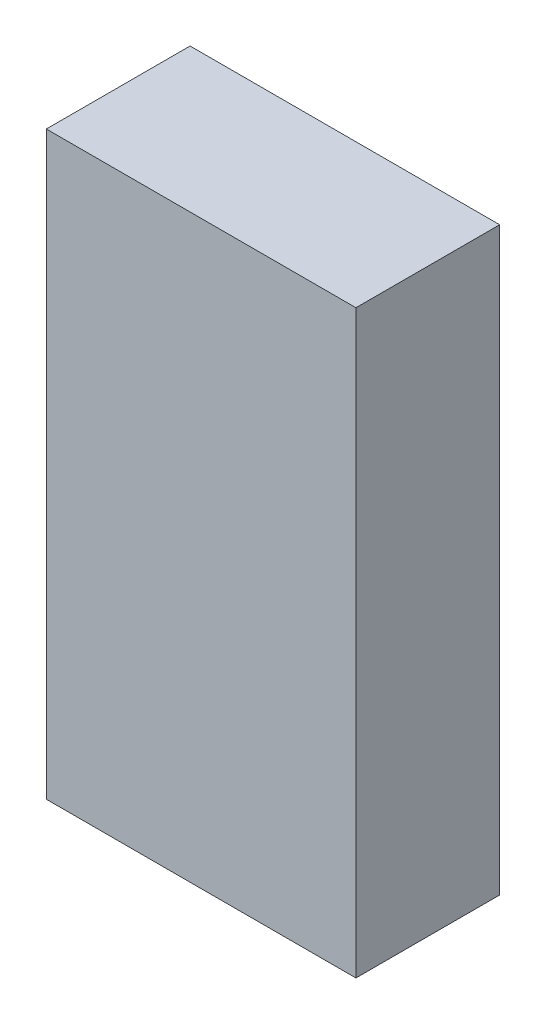
SolidWorks part; units mm, degrees
material "Aluminium"
ref_plane "Front Plane" through (0, 0, 0) normal (0, 0, 1) x (1, 0, 0)
ref_plane "Top Plane" through (0, 0, 0) normal (0, 1, 0) x (1, 0, 0)
ref_plane "Right Plane" through (0, 0, 0) normal (1, 0, 0) x (0, 0, -1)
sketch "Sketch1" plane through (0, 0, 0) normal (0, 0, 1) x (1, 0, 0)
  line L0 (-56, 105) -> (56, -105) construction
  line L1 (-56, 105) -> (56, 105)
  line L2 (-56, 105) -> (-56, -105)
  line L3 (-56, -105) -> (56, -105)
  line L4 (56, 105) -> (56, -105)
  dimension "D1" = 112
  dimension "D2" = 210
extrude "Boss-Extrude1" add sketch "Sketch1" along normal blind 52
